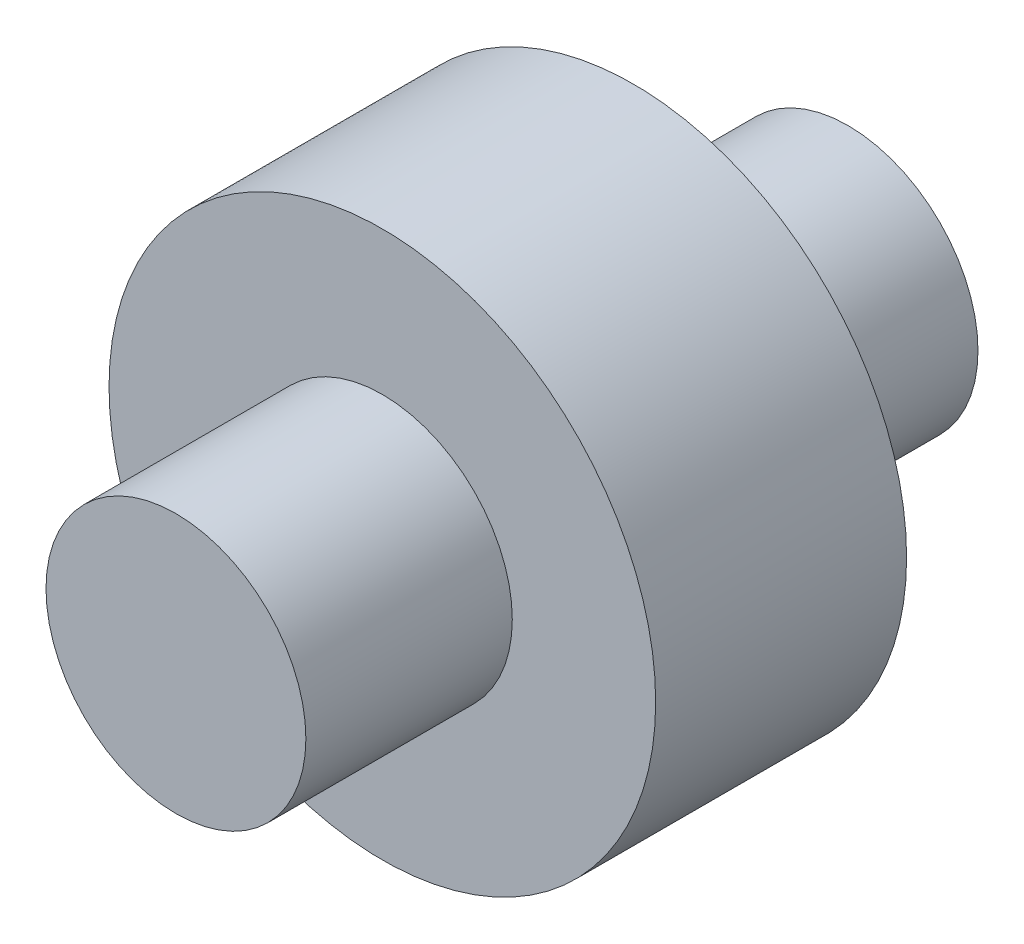
SolidWorks part; units mm, degrees
ref_plane "Front Plane" through (0, 0, 0) normal (0, 0, 1) x (1, 0, 0)
ref_plane "Top Plane" through (0, 0, 0) normal (0, 1, 0) x (1, 0, 0)
ref_plane "Right Plane" through (0, 0, 0) normal (1, 0, 0) x (0, 0, -1)
sketch "Sketch3" plane through (0, 0, 0) normal (1, 0, 0) x (0, 0, -1)
  line L0 (-6.8752, 1.8415) -> (-3.9499, 1.8415)
  line L1 (5.2388, 0) -> (-5.2388, 0) construction
  line L2 (-3.9499, 3.8735) -> (-0.3939, 3.8735)
  line L3 (-3.9499, 3.8735) -> (-3.9499, 1.8415)
  line L4 (-0.3939, 3.8735) -> (-0.3939, 1.8415)
  line L5 (-0.3939, 1.8415) -> (2.6498, 1.8415)
  line L6 (-6.8752, 1.8415) -> (-6.8752, 0)
  line L7 (2.6498, 1.8415) -> (2.6498, 0)
  line L8 (-6.8752, 0) -> (2.6498, 0) construction
  line L9 (-6.8752, 0) -> (2.6498, 0)
  dimension "D1" = 1.8415
  dimension "D2" = 3.556
  dimension "D3" = 9.525
  dimension "D4" = 3.8735
revolve "Revolve1" add sketch "Sketch3" angle 360 about L8
